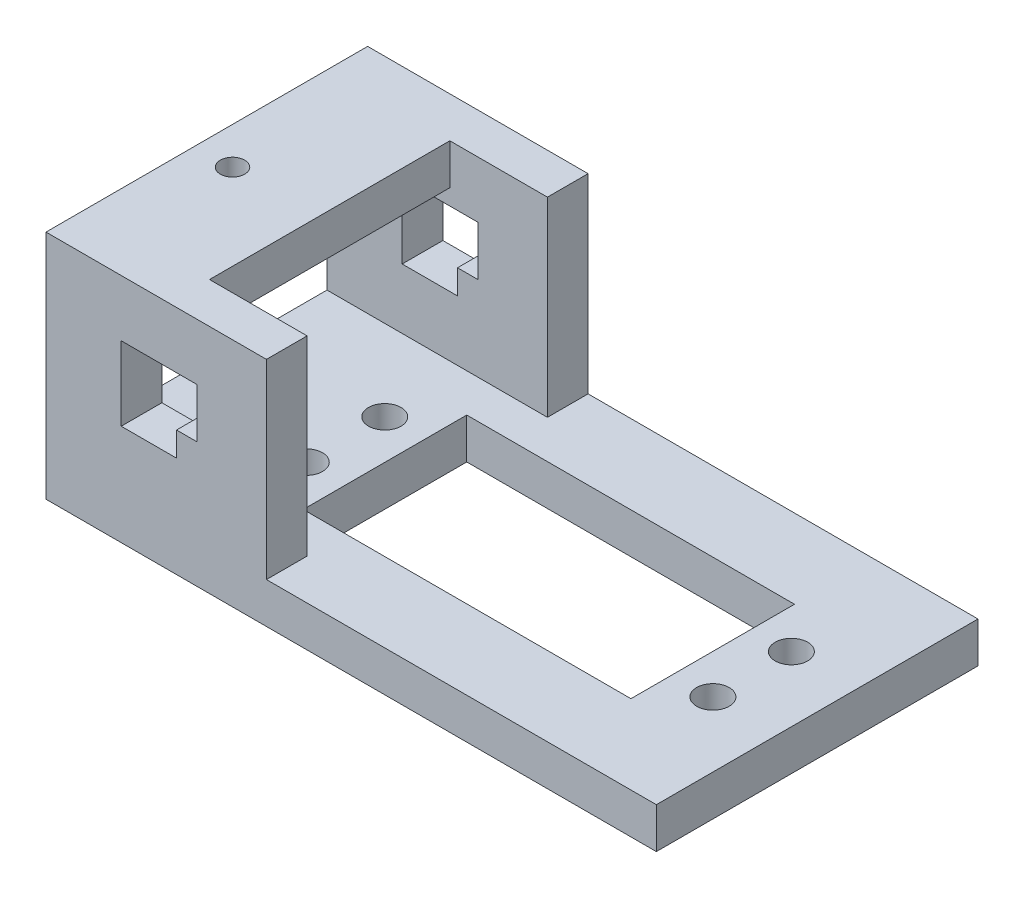
SolidWorks part; units mm, degrees
other "Markup1"
sketch "Sketch5" plane through (30.9, 36.5, -19.775) normal (0.3981, 0.9158, -0.0536) x (0.1718, -0.1318, -0.9763)
material "ABS"
ref_plane "Front Plane" through (0, 0, 0) normal (0, 0, 1) x (1, 0, 0)
ref_plane "Top Plane" through (0, 0, 0) normal (0, 1, 0) x (1, 0, 0)
ref_plane "Right Plane" through (0, 0, 0) normal (1, 0, 0) x (0, 0, -1)
sketch "Sketch1" plane through (0, 0, 0) normal (0, 1, 0) x (1, 0, 0)
  line L0 (-27, 9.91) -> (-27, 14.775) construction
  line L1 (-18, -9.9) -> (22, -9.9)
  line L2 (-27, -9.9) -> (-27, 9.91) construction
  line L3 (-18, 9.91) -> (22, 9.91)
  line L4 (32, -9.9) -> (32, 10.1)
  line L5 (-23, 19.785) -> (-23, -19.775) construction
  line L6 (-18, -9.9) -> (-27, -9.9) construction
  line L8 (32, 18.775) -> (32, 10.1)
  line L9 (32, -9.9) -> (32, -18.775)
  line L10 (31, -19.775) -> (-13.05, -19.775)
  line L11 (-27, -14.775) -> (-27, -9.9) construction
  line L12 (-18, 9.91) -> (-18, -9.9)
  line L13 (22, 9.91) -> (22, -9.9)
  line L14 (-18, 9.91) -> (-27, 9.91) construction
  line L15 (2, 9.91) -> (2, -9.9) construction
  line L19 (31, -19.775) -> (32, -19.775)
  line L21 (-13.05, 19.775) -> (31, 19.775)
  line L24 (2, 0.005) -> (-23, 0.005) construction
  line L27 (-27, 19.775) -> (-36.05, 19.775)
  line L33 (-13.05, 19.775) -> (-27, 19.775)
  line L34 (-27, 19.775) -> (-27, 14.775) construction
  line L35 (-27, -14.775) -> (-27, -19.775) construction
  line L36 (-27, -19.775) -> (-13.05, -19.775)
  line L38 (-27, 19.775) -> (-27, -19.775) construction
  line L39 (-27, -19.775) -> (-36.05, -19.775)
  line L40 (-36.05, 19.775) -> (-36.05, -19.775)
  line L41 (32, -19.775) -> (32, -18.775)
  line L42 (31, 19.775) -> (32, 19.775)
  line L43 (32, 19.775) -> (32, 18.775)
  circle A0 centre (-23, -4.82) radius 2
  circle A1 centre (-23, 4.83) radius 2
  circle A2 centre (27, -4.82) radius 2
  circle A3 centre (27, 4.83) radius 2
  point P0 (0, 0)
  point P14 (-23, -4.82)
  point P17 (-23, -4.82)
  point P18 (-23.4733, -9.9)
  point P19 (-23, 4.83)
  dimension "D11" = 4
  dimension "D12" = 4
  dimension "D3" = 5
  dimension "D4" = 5
  dimension "D1" = 40
  dimension "D2" = 20
  dimension "D5" = 9.65
  dimension "D6" = 9
  dimension "D7" = 5
  dimension "D8" = 25
  dimension "D9" = 5.08
  dimension "D10" = 5.08
  dimension "D13" = 23
  dimension "D14" = 9.05
extrude "Boss-Extrude1" add sketch "Sketch1" along normal blind 5
sketch "Sketch2" plane through (0, 5, 0) normal (0, 1, 0) x (1, 0, 0)
  line L0 (-36.05, 19.775) -> (-36.05, -19.775) construction
  line L1 (-36.05, -19.775) -> (-12.9435, -19.775)
  line L2 (-36.05, -19.775) -> (-36.05, -14.775)
  line L3 (-36.05, -14.775) -> (-12.9435, -14.775)
  line L4 (-12.9435, -19.775) -> (-12.9435, -14.775)
  line L5 (-12.9435, 14.775) -> (-36.05, 14.775)
  line L6 (-12.9435, 14.775) -> (-12.9435, 19.775)
  line L7 (-12.9435, 19.775) -> (-36.05, 19.775)
  line L8 (-36.05, 14.775) -> (-36.05, 19.775)
  line L9 (32, 19.775) -> (-36.05, 19.775) construction
  dimension "D1" = 5
  dimension "D2" = 5
extrude "Boss-Extrude2" add sketch "Sketch2" along normal blind 18.45
sketch "Sketch3" plane through (0, 0, 19.775) normal (0, 0, 1) x (1, 0, 0)
  line L1 (-36.05, 23.45) -> (-12.9435, 23.45)
  line L2 (-36.05, 23.45) -> (-36.05, 28.45)
  line L3 (-36.05, 28.45) -> (-12.9435, 28.45)
  line L4 (-12.9435, 23.45) -> (-12.9435, 28.45)
  dimension "D1" = 5
extrude "Boss-Extrude3" add sketch "Sketch3" against normal up to surface (39.55 mm away) up to face at (-5.6645, 9.4833, -19.775)
sketch "Sketch4" plane through (0, 0, 19.775) normal (0, 0, 1) x (1, 0, 0)
  line L0 (-12.9435, 5) -> (-36.05, 5) construction
  line L1 (-24.05, 21.45) -> (-30.75, 21.45)
  line L2 (-24.05, 15.45) -> (-21.55, 15.45)
  line L3 (-21.55, 15.45) -> (-21.55, 21.45)
  line L4 (-21.55, 21.45) -> (-24.05, 21.45)
  line L7 (-30.75, 21.45) -> (-30.75, 15.45)
  line L8 (-36.05, 28.45) -> (-36.05, 0) construction
  line L10 (-30.75, 15.45) -> (-30.75, 12.45)
  line L11 (-30.75, 12.45) -> (-24.05, 12.45)
  line L12 (-24.05, 15.45) -> (-24.05, 12.45)
  dimension "D1" = 10.45
  dimension "D2" = 3
  dimension "D3" = 6
  dimension "D4" = 2.5
  dimension "D6" = 5.3
  dimension "D7" = 3
  dimension "D8" = 6.7
extrude "Cut-Extrude1" cut sketch "Sketch4" against normal up to surface (39.55 mm away)
sketch "Sketch6" plane through (0, 5, 0) normal (0, 1, 0) x (1, 0, 0)
  line L1 (-24.9435, -14.775) -> (-12.9435, -14.775)
  line L2 (-24.9435, -14.775) -> (-24.9435, 14.775)
  line L3 (-24.9435, 14.775) -> (-12.9435, 14.775)
  line L4 (-12.9435, -14.775) -> (-12.9435, 14.775)
  dimension "D1" = 12
extrude "Cut-Extrude2" cut sketch "Sketch6" along normal up to surface (23.45 mm away) up to face at (-24.4967, 28.45, 0)
sketch "Sketch7" plane through (0, 0, 19.775) normal (0, 0, 1) x (1, 0, 0)
  line L0 (-24.05, 21.5) -> (-30.8, 21.5)
  line L1 (-30.8, 21.5) -> (-30.8, 15.45)
  line L2 (-30.8, 15.45) -> (-30.8, 12.4)
  line L3 (-30.8, 12.4) -> (-24, 12.4)
  line L4 (-24, 12.4) -> (-24, 15.4)
  line L5 (-24, 15.4) -> (-21.5, 15.4)
  line L6 (-21.5, 15.4) -> (-21.5, 21.5)
  line L7 (-21.5, 21.5) -> (-24.05, 21.5)
  line L8 (-24.05, 21.45) -> (-30.75, 21.45)
  line L9 (-30.75, 21.45) -> (-30.75, 15.45)
  line L10 (-30.75, 15.45) -> (-30.75, 12.45)
  line L11 (-30.75, 12.45) -> (-24.05, 12.45)
  line L12 (-24.05, 12.45) -> (-24.05, 15.45)
  line L13 (-24.05, 15.45) -> (-21.55, 15.45)
  line L14 (-21.55, 15.45) -> (-21.55, 21.45)
  line L15 (-21.55, 21.45) -> (-24.05, 21.45)
  line L16 (-24.05, 21.45) -> (-30.75, 21.45)
  line L17 (-30.75, 21.45) -> (-30.75, 15.45)
  line L18 (-30.75, 15.45) -> (-30.75, 12.45)
  line L19 (-30.75, 12.45) -> (-24.05, 12.45)
  line L20 (-24.05, 12.45) -> (-24.05, 15.45)
  line L21 (-24.05, 15.45) -> (-21.55, 15.45)
  line L22 (-21.55, 15.45) -> (-21.55, 21.45)
  line L23 (-21.55, 21.45) -> (-24.05, 21.45)
  dimension "D1" = 0
  dimension "D2" = 0.05
extrude "Cut-Extrude3" cut sketch "Sketch7" against normal up to surface (39.55 mm away)
sketch "Sketch9" plane through (-36.05, 0, 0) normal (-1, 0, 0) x (0, 0, 1)
  line L0 (14.775, 23.45) -> (14.775, 5) construction
  line L1 (-14.775, 5) -> (14.775, 5) construction
  line L2 (-14.775, 23.45) -> (-14.775, 5) construction
  line L3 (-14.775, 23.45) -> (14.775, 23.45) construction
  line L4 (19.775, 0) -> (19.775, 28.45)
  line L5 (19.775, 28.45) -> (-19.775, 28.45)
  line L6 (-19.775, 28.45) -> (-19.775, 0)
  line L7 (-19.775, 0) -> (19.775, 0)
  line L8 (19.775, 0) -> (19.775, 28.45)
  line L9 (19.775, 28.45) -> (-19.775, 28.45)
  line L10 (-19.775, 28.45) -> (-19.775, 0)
  line L11 (-19.775, 0) -> (19.775, 0)
  line L12 (14.775, 23.45) -> (14.775, 5)
  line L13 (-14.775, 5) -> (14.775, 5)
  line L14 (-14.775, 23.45) -> (-14.775, 5)
  line L15 (-14.775, 23.45) -> (14.775, 23.45)
  dimension "D1" = 0
extrude "Boss-Extrude4" add sketch "Sketch9" along normal blind 4
sketch "Sketch11" plane through (32, 0, 0) normal (1, 0, 0) x (0, 0, -1)
  line L4 (-19.775, 0) -> (19.775, 0)
  line L5 (19.775, 0) -> (19.775, 5)
  line L6 (19.775, 5) -> (-19.775, 5)
  line L7 (-19.775, 5) -> (-19.775, 0)
  line L8 (-19.775, 0) -> (19.775, 0)
  line L9 (19.775, 0) -> (19.775, 5)
  line L10 (19.775, 5) -> (-19.775, 5)
  line L11 (-19.775, 5) -> (-19.775, 0)
  dimension "D1" = 0
extrude "Boss-Extrude5" add sketch "Sketch11" along normal blind 3
sketch "Sketch12" plane through (0, 5, 0) normal (0, 1, 0) x (1, 0, 0)
  line L0 (22, -9.9) -> (22, 9.91) construction
  line L1 (-18, -9.9) -> (22, -9.9) construction
  line L2 (-18, 9.91) -> (-18, -9.9) construction
  line L3 (22, 9.91) -> (-18, 9.91) construction
  line L4 (22, -9.9) -> (22, 9.91)
  line L5 (-18, -9.9) -> (22, -9.9)
  line L6 (-18, 9.91) -> (-18, -9.9)
  line L7 (22, 9.91) -> (-18, 9.91)
  line L8 (22.15, 10.06) -> (-18.15, 10.06)
  line L9 (-18.15, 10.06) -> (-18.15, -10.05)
  line L10 (-18.15, -10.05) -> (22.15, -10.05)
  line L11 (22.15, -10.05) -> (22.15, 10.06)
extrude "Cut-Extrude4" cut sketch "Sketch12" against normal up to surface (5 mm away) up to face at (-2.525, 0, 0)
sketch "Sketch13" plane through (0, 28.45, 0) normal (0, 1, 0) x (1, 0, 0)
  line L0 (-24.9435, 14.775) -> (-40.05, 14.775) construction
  line L1 (-40.05, -19.775) -> (-40.05, 19.775) construction
  line L2 (-40.05, 14.775) -> (-12.9435, 14.775) construction
  line L3 (-24.9435, -14.775) -> (-40.05, -14.775) construction
  line L4 (-35.4967, 14.775) -> (-35.4967, 1.105) construction
  line L5 (-35.4967, 1.105) -> (-35.4967, -3.895) construction
  line L6 (-35.4967, -3.895) -> (-35.4967, -5.895) construction
  line L7 (-35.4967, 1.105) -> (-35.4967, 3.105) construction
  circle A0 centre (-35.4967, -1.395) radius 1.5
  dimension "D5" = 3
  dimension "D1" = 13.67
  dimension "D2" = 5
  dimension "D3" = 2
  dimension "D4" = 2
  dimension "D6" = 4.5533
extrude "Cut-Extrude5" cut sketch "Sketch13" against normal up to surface (5 mm away) up to face at (-32.4967, 23.45, 0)
